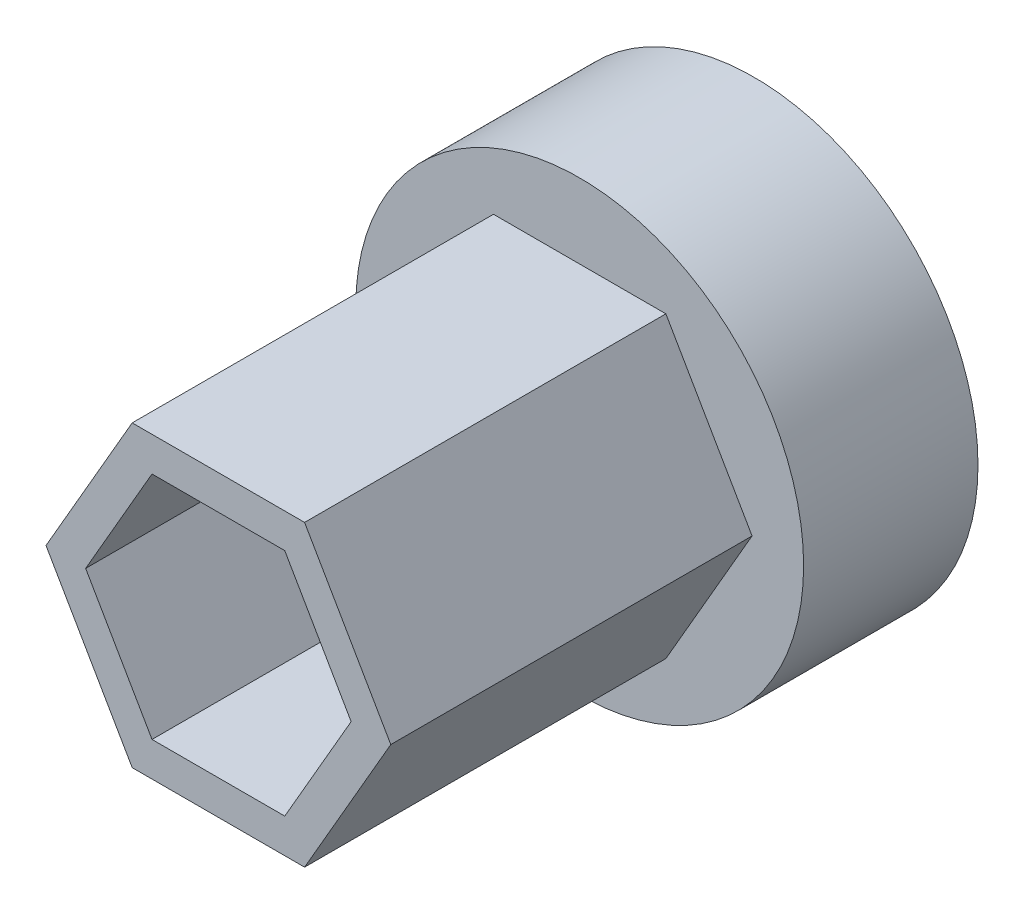
SolidWorks part; units mm, degrees
material "PET"
ref_plane "Front Plane" through (0, 0, 0) normal (0, 0, 1) x (1, 0, 0)
ref_plane "Top Plane" through (0, 0, 0) normal (0, 1, 0) x (1, 0, 0)
ref_plane "Right Plane" through (0, 0, 0) normal (1, 0, 0) x (0, 0, -1)
sketch "Sketch1" plane through (0, 0, 0) normal (0, 0, 1) x (1, 0, 0)
  line L1 (5.6459, 0) -> (2.823, 4.8895)
  line L2 (2.823, 4.8895) -> (-2.823, 4.8895)
  line L3 (-2.823, 4.8895) -> (-5.6459, 0)
  line L4 (-5.6459, 0) -> (-2.823, -4.8895)
  line L5 (-2.823, -4.8895) -> (2.823, -4.8895)
  line L6 (2.823, -4.8895) -> (5.6459, 0)
  line L7 (7.3323, 0) -> (3.6662, 6.35)
  line L8 (3.6662, 6.35) -> (-3.6662, 6.35)
  line L9 (-3.6662, 6.35) -> (-7.3323, 0)
  line L10 (-7.3323, 0) -> (-3.6662, -6.35)
  line L11 (-3.6662, -6.35) -> (3.6662, -6.35)
  line L12 (3.6662, -6.35) -> (7.3323, 0)
  circle A0 centre (0, 0) radius 4.8895 construction
  circle A2 centre (0, 0) radius 6.35 construction
  point P1 (0, 0)
  dimension "D1" = 9.779
  dimension "D2" = 12.7
extrude "Boss-Extrude1" add sketch "Sketch1" along normal blind 15.367
sketch "Sketch2" plane through (0, 0, 0) normal (0, 0, -1) x (-1, 0, 0)
  line L1 (5.6459, 0) -> (2.823, 4.8895)
  line L2 (2.823, 4.8895) -> (-2.823, 4.8895)
  line L3 (-2.823, 4.8895) -> (-5.6459, 0)
  line L4 (-5.6459, 0) -> (-2.823, -4.8895)
  line L5 (-2.823, -4.8895) -> (2.823, -4.8895)
  line L6 (2.823, -4.8895) -> (5.6459, 0)
  circle A0 centre (0, 0) radius 4.8895 construction
  circle A1 centre (0, 0) radius 9.525
  dimension "D1" = 19.05
extrude "Boss-Extrude2" add sketch "Sketch2" along normal blind 7.4168
